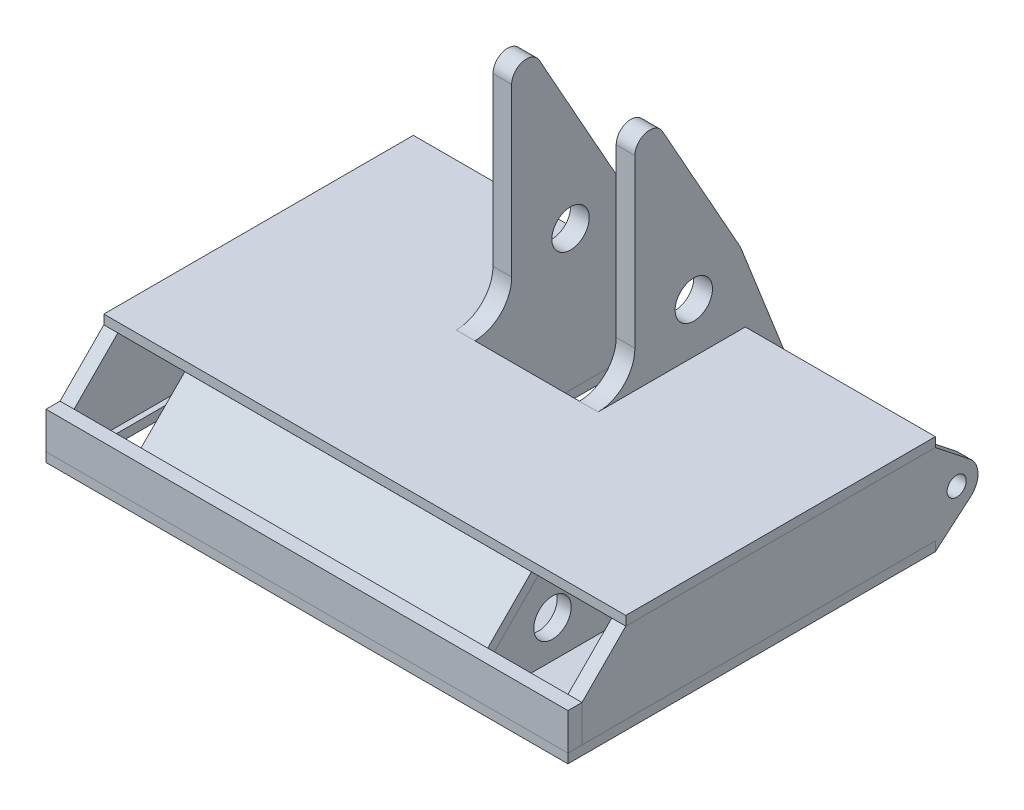
SolidWorks part; units mm, degrees
material "2024-T4"
ref_plane "Front Plane" through (0, 0, 0) normal (0, 0, 1) x (1, 0, 0)
ref_plane "Top Plane" through (0, 0, 0) normal (0, 1, 0) x (1, 0, 0)
ref_plane "Right Plane" through (0, 0, 0) normal (1, 0, 0) x (0, 0, -1)
sketch "Side View" plane through (0, 0, 0) normal (1, 0, 0) x (0, 0, -1)
  line L1 (165, 199.6593) -> (165, 86.35)
  line L3 (140, 55) -> (29.7536, 55)
  line L4 (240, 0) -> (240, 55) construction
  line L5 (0, 0) -> (240, 0)
  line L9 (183.7233, 204.5484) -> (235.5315, 112.1122)
  line L10 (179.9201, 117.2092) -> (110.2141, 38.4935) construction
  line L11 (29.7536, 55) -> (140, 55)
  line L12 (29.7536, 55) -> (29.7536, 61.35) construction
  line L13 (29.7536, 61.35) -> (140, 61.35) construction
  line L14 (140, 55) -> (140, 61.35)
  line L15 (0, 0) -> (240, 0) construction
  line L16 (0, 0) -> (0, -6.35) construction
  line L17 (0, -6.35) -> (240, -6.35) construction
  line L18 (240, 0) -> (240, -6.35) construction
  line L19 (223.5253, 67.0883) -> (135.9217, 8.9446) construction
  line L20 (240, 55) -> (240, 0) construction
  line L21 (240, 0) -> (240, -6.35)
  line L22 (240, 55) -> (230.475, 55) construction
  line L23 (230.475, 55) -> (230.475, 0) construction
  line L24 (13.588, 51.1116) -> (-9.525, 27.8072) construction
  line L25 (240, -6.35) -> (263.8895, 13.9507)
  line L26 (267.9974, 30.2982) -> (237.5799, 107.7886)
  line L27 (13.588, 51.1116) -> (167.8998, 206.7011) construction
  line L28 (190.9625, 46.4) -> (39.5125, 46.4) construction
  line L29 (39.5125, 25.4) -> (190.9625, 25.4) construction
  line L30 (190.9625, 4.4) -> (39.5125, 4.4) construction
  line L31 (-9.525, 25) -> (-9.525, -6.35) construction
  line L32 (-9.525, -6.35) -> (0, -6.35) construction
  line L33 (0, 0) -> (0, 25)
  line L34 (0, 25) -> (29.7536, 55)
  line L35 (-9.525, 25) -> (0, 25) construction
  line L36 (-4.5086, 29.4716) -> (25.245, 59.4716) construction
  line L37 (0, 25) -> (-4.5086, 29.4716) construction
  line L38 (29.7536, 55) -> (25.245, 59.4716) construction
  circle A1 centre (205, 95) radius 12.7
  circle A2 centre (205, 95) radius 100 construction
  arc A3 (183.7233, 204.5484) -> (165, 199.6593) centre (175, 199.6593) ccw
  arc A4 (140, 61.35) -> (165, 86.35) centre (140, 86.35) ccw
  circle A5 centre (125, 25.4) radius 19.75 construction
  circle A6 centre (205, 95) radius 33.5 construction
  circle A7 centre (39.5125, 25.4) radius 36.5125 construction
  circle A8 centre (190.9625, 25.4) radius 36.5125 construction
  circle A9 centre (254.5, 25) radius 6.5
  arc A11 (263.8895, 13.9507) -> (267.9974, 30.2982) centre (254.5, 25) ccw
  arc A13 (237.5799, 107.7886) -> (235.5315, 112.1122) centre (205, 95) ccw
  circle A14 centre (190.9625, 25.4) radius 21 construction
  circle A15 centre (39.5125, 25.4) radius 21 construction
  point P16 (240, 0)
  point P24 (165, 237.9546)
  point P40 (217.1923, 0)
  point P43 (23.0635, 0)
  point P45 (164.7327, 0)
  point P49 (65.7423, 0)
  point P50 (13.2827, 0)
  point P52 (0, 0)
  point P53 (250, 105.4809)
  point P56 (0, 0)
  dimension "D1" = 25.4
  dimension "D3" = 200
  dimension "D8" = 10
  dimension "D11" = 39.5
  dimension "D15" = 67
  dimension "D17" = 73.025
  dimension "D16" = 13
  dimension "D29" = 73.025
  dimension "D31" = 42
  dimension "D32" = 42
  dimension "D28" = 35
  dimension "D2" = 55
  dimension "D9" = 6.35
  dimension "D10" = 25
  dimension "D14" = 40
  dimension "D5" = 5
  dimension "D4" = 35
  dimension "D18" = 4.7625
  dimension "D7" = 5
  dimension "D20" = 3
  dimension "D22" = 25
  dimension "D26" = 9.525
  dimension "D13" = 80
  dimension "D19" = 3
  dimension "D6" = 240
  dimension "D24" = 8
  dimension "D25" = 8
  dimension "D27" = 25
  dimension "D30" = 4.7625
  dimension "D34" = 151.45
  dimension "D21" = 6.35
sketch "Top View" plane through (0, 0, 0) normal (0, 1, 0) x (1, 0, 0)
  line L0 (0, 120) -> (0, 0) construction
  line L1 (177.25, 0) -> (167.725, 0)
  line L2 (177.25, 0) -> (177.25, 240)
  line L3 (177.25, 240) -> (35.5, 240)
  line L4 (-177.25, 0) -> (-177.25, 240)
  line L5 (177.25, 0) -> (-177.25, 240) construction
  line L6 (177.25, 240) -> (-177.25, 0) construction
  line L9 (-35.5, 240) -> (-35.5, 0)
  line L11 (35.5, 240) -> (35.5, 0)
  line L13 (-167.725, 230.475) -> (-167.725, 0)
  line L15 (-117.725, 230.475) -> (-117.725, 0)
  line L17 (167.725, 230.475) -> (117.725, 230.475)
  line L18 (167.725, 230.475) -> (167.725, 0)
  line L19 (-35.5, 240) -> (-177.25, 240)
  line L20 (-167.725, 0) -> (-177.25, 0)
  line L22 (167.725, 230.475) -> (48.2, 230.475)
  line L26 (-48.2, 230.475) -> (-167.725, 230.475)
  line L29 (167.725, 0) -> (-108.2, 0)
  line L33 (-150.8375, 190.9625) -> (-150.8375, 229.0625) construction
  line L35 (-161.95, 77.6125) -> (-161.95, 1.4125) construction
  line L36 (108.2, 165.9625) -> (53.2, 165.9625) construction
  line L37 (-108.2, 215.9625) -> (-53.2, 215.9625) construction
  line L38 (-108.2, 215.9625) -> (-108.2, 165.9625) construction
  line L39 (-108.2, 165.9625) -> (-53.2, 165.9625) construction
  line L40 (-53.2, 215.9625) -> (-53.2, 165.9625) construction
  line L41 (53.2, 215.9625) -> (53.2, 165.9625) construction
  line L42 (108.2, 215.9625) -> (53.2, 215.9625) construction
  line L43 (108.2, 215.9625) -> (108.2, 165.9625) construction
  line L44 (161.95, 152.8625) -> (139.725, 152.8625) construction
  line L45 (-161.95, 229.0625) -> (-139.725, 229.0625) construction
  line L46 (-161.95, 229.0625) -> (-161.95, 152.8625) construction
  line L47 (-161.95, 152.8625) -> (-139.725, 152.8625) construction
  line L48 (-139.725, 229.0625) -> (-139.725, 152.8625) construction
  line L49 (-161.95, 229.0625) -> (-139.725, 152.8625) construction
  line L50 (-161.95, 152.8625) -> (-139.725, 229.0625) construction
  line L51 (139.725, 229.0625) -> (139.725, 152.8625) construction
  line L52 (161.95, 229.0625) -> (139.725, 229.0625) construction
  line L53 (161.95, 229.0625) -> (161.95, 152.8625) construction
  line L54 (-108.2, 240) -> (-108.2, 0) construction
  line L56 (-139.725, 77.6125) -> (-139.725, 1.4125) construction
  line L57 (-48.2, 230.475) -> (-48.2, 0)
  line L58 (48.2, 230.475) -> (48.2, 0)
  line L59 (-108.2, 0) -> (-167.725, 0)
  line L60 (-117.725, 230.475) -> (-117.725, -9.525) construction
  line L61 (105.4111, 240) -> (167.725, 0) construction
  line L62 (-35.5, 240) -> (35.5, 240)
  line L63 (-48.2, 230.475) -> (48.2, 230.475) construction
  line L65 (167.725, 240) -> (105.4111, 240) construction
  line L66 (-167.725, 240) -> (-108.2, 240) construction
  line L67 (-167.725, 230.475) -> (-117.725, 230.475) construction
  line L68 (-161.95, 1.4125) -> (-139.725, 1.4125) construction
  line L69 (-161.95, 39.5125) -> (-139.725, 39.5125) construction
  line L70 (-177.25, 0) -> (-177.25, -9.525)
  line L71 (-119.725, 9.5125) -> (-119.725, 69.5125) construction
  line L72 (-119.725, 160.9625) -> (-139.725, 160.9625) construction
  line L73 (-119.725, 160.9625) -> (-119.725, 220.9625) construction
  line L74 (-119.725, 220.9625) -> (-139.725, 220.9625) construction
  line L75 (-139.725, 160.9625) -> (-139.725, 220.9625) construction
  line L76 (-119.725, 160.9625) -> (-139.725, 220.9625) construction
  line L77 (-119.725, 220.9625) -> (-139.725, 160.9625) construction
  line L78 (-119.725, 9.5125) -> (-139.725, 9.5125) construction
  line L79 (-139.725, 9.5125) -> (-139.725, 69.5125) construction
  line L80 (-119.725, 69.5125) -> (-139.725, 69.5125) construction
  line L81 (-108.2, 230.475) -> (-108.2, 0)
  line L82 (-161.95, 77.6125) -> (-139.725, 77.6125) construction
  line L83 (-161.95, 77.6125) -> (-139.725, 77.6125) construction
  line L84 (-177.25, -9.525) -> (177.25, -9.525)
  line L85 (48.2, 145) -> (155.2, 145) construction
  line L86 (48.2, 145) -> (48.2, 105) construction
  line L87 (48.2, 105) -> (155.2, 105) construction
  line L88 (155.2, 145) -> (155.2, 105) construction
  line L89 (1.5875, 105) -> (-23.8125, 105) construction
  line L90 (1.5875, 105) -> (1.5875, 305) construction
  line L91 (1.5875, 305) -> (-23.8125, 305) construction
  line L92 (-23.8125, 105) -> (-23.8125, 305) construction
  line L93 (1.5875, 105) -> (-23.8125, 305) construction
  line L94 (1.5875, 305) -> (-23.8125, 105) construction
  line L95 (177.25, -9.525) -> (177.25, 0)
  line L96 (0, 105) -> (0, 305) construction
  line L97 (-11.1125, 205) -> (11.1125, 205) construction
  line L98 (20.6375, 171.5) -> (1.5875, 171.5) construction
  line L99 (20.6375, 171.5) -> (20.6375, 238.5) construction
  line L100 (20.6375, 238.5) -> (1.5875, 238.5) construction
  line L101 (1.5875, 171.5) -> (1.5875, 238.5) construction
  line L102 (20.6375, 171.5) -> (1.5875, 238.5) construction
  line L103 (20.6375, 238.5) -> (1.5875, 171.5) construction
  line L104 (180.0389, -9.525) -> (-117.725, -9.525) construction
  line L105 (117.725, 230.475) -> (180.0389, -9.525) construction
  line L106 (119.725, 160.9625) -> (139.725, 160.9625) construction
  line L107 (119.725, 160.9625) -> (119.725, 220.9625) construction
  line L108 (119.725, 220.9625) -> (139.725, 220.9625) construction
  line L109 (108.2, 230.475) -> (108.2, 0)
  line L110 (117.725, 230.475) -> (117.725, 0)
  line L111 (119.725, 9.5125) -> (119.725, 69.5125) construction
  line L112 (119.725, 69.5125) -> (139.725, 69.5125) construction
  line L113 (119.725, 9.5125) -> (139.725, 9.5125) construction
  line L114 (161.95, 1.4125) -> (139.725, 1.4125) construction
  line L115 (161.95, 77.6125) -> (139.725, 77.6125) construction
  line L116 (161.95, 77.6125) -> (161.95, 1.4125) construction
  line L117 (139.725, 77.6125) -> (139.725, 1.4125) construction
  line L118 (-167.725, 230.475) -> (-167.725, 240)
  line L119 (-48.2, 230.475) -> (-48.2, 240)
  line L120 (48.2, 230.475) -> (48.2, 240)
  line L121 (167.725, 230.475) -> (167.725, 240)
  line L122 (0, 171.5) -> (0, 238.5) construction
  line L123 (-35.5, 145) -> (35.5, 145)
  line L125 (-107.2, 162) -> (-51.2, 162) construction
  line L126 (-107.2, 162) -> (-107.2, 2) construction
  line L127 (-107.2, 2) -> (-51.2, 2) construction
  line L128 (-51.2, 162) -> (-51.2, 2) construction
  line L129 (-35.5, 104) -> (35.5, 104)
  line L130 (-35.5, 104) -> (-35.5, 94.475)
  line L131 (-35.5, 94.475) -> (35.5, 94.475)
  line L132 (35.5, 104) -> (35.5, 94.475)
  point P0 (0, 0)
  point P44 (-150.8375, 190.9625)
  point P45 (-167.725, 115.2375)
  point P58 (-129.725, 190.9625)
  point P60 (-53.2, 190.9625)
  point P76 (0, 205)
  point P77 (11.1125, 205)
  point P78 (-11.1125, 205)
  point P87 (155.2, 125)
  dimension "D5" = 50
  dimension "D6" = 9.525
  dimension "D10" = 22.225
  dimension "D11" = 76.2
  dimension "D12" = 50
  dimension "D8" = 9.525
  dimension "D15" = 12.7
  dimension "D7" = 55
  dimension "D4" = 20
  dimension "D14" = 2
  dimension "D16" = 60
  dimension "D3" = 71
  dimension "D18" = 9.525
  dimension "D19" = 40
  dimension "D20" = 107
  dimension "D21" = 25.4
  dimension "D22" = 19.05
  dimension "D24" = 9.525
  dimension "D25" = 60
  dimension "D23" = 56
  dimension "D26" = 160
  dimension "D27" = 2
  dimension "D28" = 3
  dimension "D29" = 9.525
  dimension "D30" = 1
  dimension "D31" = 60
  dimension "D32" = 354.5
  dimension "D9" = 9.525
  dimension "D13" = 2
  dimension "D17" = 2
ref_plane "Left Weapon Wall Plane" through (-35.5, 0, 0) normal (1, 0, 0) x (0, 0, -1)
ref_plane "Right Weapon Wall Plane" through (35.5, 0, 0) normal (1, 0, 0) x (0, 0, -1)
ref_plane "Front Wall Plane" through (0, 0, -240) normal (0, 0, 1) x (1, 0, 0)
ref_plane "Rear Wall Plane" through (0, 0, 9.525) normal (0, 0, 1) x (1, 0, 0)
ref_plane "Left Motor Wall Plane" through (-108.2, 0, 0) normal (1, 0, 0) x (0, 0, -1)
ref_plane "Right Motor Wall Plane" through (108.2, 0, 0) normal (1, 0, 0) x (0, 0, -1)
ref_plane "Left Outside Wall Plane" through (-177.25, 0, 0) normal (1, 0, 0) x (0, 0, -1)
ref_plane "Wheel Center" through (-150.8375, 0, 0) normal (1, 0, 0) x (0, 0, -1)
ref_plane "Angled Back Plane" through (0, 12.3969, 12.4996) normal (0, -0.7042, -0.71) x (0, 0.71, -0.7042)
ref_plane "Top Plate Plane" through (0, 55, 0) normal (0, 1, 0) x (1, 0, 0)
ref_plane "Shielding Plate Plane" through (0, 0, -104) normal (0, 0, 1) x (1, 0, 0)
sketch "Sketch14" plane through (0, 0, -104) normal (0, 0, 1) x (1, 0, 0)
  line L1 (-35.5, 0) -> (35.5, 0)
  line L2 (-35.5, 0) -> (-35.5, 55)
  line L3 (-35.5, 55) -> (35.5, 55)
  line L4 (35.5, 0) -> (35.5, 55)
extrude "Boss-Extrude9" add sketch "Sketch14" along normal up to vertex (9.525 mm away) up to point (-35.5, 0, -94.475)
sketch "Sketch2" plane through (0, 0, 0) normal (0, 1, 0) x (1, 0, 0)
  line L0 (177.25, -9.525) -> (177.25, 0) construction
  line L1 (-177.25, 0) -> (-177.25, -9.525) construction
  line L2 (-177.25, -9.525) -> (177.25, -9.525) construction
  line L3 (177.25, 0) -> (177.25, 240) construction
  line L4 (177.25, 240) -> (35.5, 240) construction
  line L5 (35.5, 240) -> (35.5, 0) construction
  line L6 (-35.5, 145) -> (35.5, 145) construction
  line L7 (-35.5, 240) -> (-35.5, 0) construction
  line L8 (-35.5, 240) -> (-177.25, 240) construction
  line L9 (-177.25, 0) -> (-177.25, 240) construction
  line L10 (177.25, -9.525) -> (177.25, 0)
  line L11 (-177.25, 0) -> (-177.25, -9.525)
  line L12 (-177.25, -9.525) -> (177.25, -9.525)
  line L13 (177.25, 0) -> (177.25, 240)
  line L14 (177.25, 240) -> (35.5, 240)
  line L15 (35.5, 240) -> (35.5, 145)
  line L16 (-35.5, 145) -> (35.5, 145)
  line L17 (-35.5, 240) -> (-35.5, 145)
  line L18 (-35.5, 240) -> (-177.25, 240)
  line L19 (-177.25, 0) -> (-177.25, 240)
  line L20 (-161.95, 1.4125) -> (-139.725, 1.4125) construction
  line L21 (-139.725, 77.6125) -> (-139.725, 1.4125) construction
  line L22 (-161.95, 77.6125) -> (-139.725, 77.6125) construction
  line L23 (-161.95, 77.6125) -> (-161.95, 1.4125) construction
  line L24 (-139.725, 229.0625) -> (-139.725, 152.8625) construction
  line L25 (-163.95, 219.1923) -> (-137.725, 219.1923)
  line L26 (-137.725, 219.1923) -> (-137.725, 162.7327)
  line L27 (-161.95, 229.0625) -> (-161.95, 152.8625) construction
  line L28 (-161.95, 1.4125) -> (-139.725, 1.4125) construction
  line L29 (-139.725, 77.6125) -> (-139.725, 1.4125) construction
  line L30 (-161.95, 77.6125) -> (-139.725, 77.6125) construction
  line L31 (-161.95, 77.6125) -> (-161.95, 1.4125) construction
  line L32 (-139.725, 217.1923) -> (-139.725, 164.7327) construction
  line L35 (-161.95, 217.1923) -> (-161.95, 164.7327) construction
  line L36 (-161.95, 217.1923) -> (-139.725, 217.1923) construction
  line L37 (-150.8375, 190.9625) -> (-129.725, 190.9625) construction
  line L38 (-161.95, 164.7327) -> (-139.725, 164.7327) construction
  line L39 (-163.95, 162.7327) -> (-137.725, 162.7327)
  line L40 (-163.95, 219.1923) -> (-163.95, 162.7327)
  line L41 (-137.725, 67.7423) -> (-137.725, 11.2827)
  line L42 (-163.95, 67.7423) -> (-137.725, 67.7423)
  line L43 (-163.95, 67.7423) -> (-163.95, 11.2827)
  line L44 (-163.95, 11.2827) -> (-137.725, 11.2827)
  line L45 (-150.8375, 39.5125) -> (-129.725, 39.5125) construction
  line L46 (-161.95, 39.5125) -> (-139.725, 39.5125) construction
  dimension "D1" = 2
  dimension "D2" = 2
extrude "Bottom Plate" add sketch "Sketch2" against normal up to vertex (6.35 mm away) up to point (0, -6.35, 0)
sketch "Sketch3" plane through (-35.5, 0, 0) normal (1, 0, 0) x (0, 0, -1)
  line L0 (140, 55) -> (29.7536, 55) construction
  line L2 (140, 55) -> (140, 61.35) construction
  line L3 (165, 199.6593) -> (165, 86.35) construction
  line L4 (183.7233, 204.5484) -> (235.5315, 112.1122) construction
  line L7 (0, 0) -> (240, 0) construction
  line L8 (0, 0) -> (0, 25) construction
  line L9 (0, 25) -> (29.7536, 55) construction
  line L10 (140, 55) -> (29.7536, 55)
  line L12 (140, 55) -> (140, 61.35)
  line L13 (165, 199.6593) -> (165, 86.35)
  line L14 (183.7233, 204.5484) -> (235.5315, 112.1122)
  line L17 (0, 0) -> (240, 0)
  line L18 (0, 0) -> (0, 25)
  line L19 (0, 25) -> (29.7536, 55)
  line L20 (240, 0) -> (240, -6.35) construction
  line L21 (240, -6.35) -> (263.8895, 13.9507) construction
  line L22 (267.9974, 30.2982) -> (237.5799, 107.7886) construction
  line L23 (240, 0) -> (240, -6.35)
  line L24 (240, -6.35) -> (263.8895, 13.9507)
  line L25 (267.9974, 30.2982) -> (237.5799, 107.7886)
  arc A0 (140, 61.35) -> (165, 86.35) centre (140, 86.35) ccw construction
  arc A1 (183.7233, 204.5484) -> (165, 199.6593) centre (175, 199.6593) ccw construction
  arc A3 (140, 61.35) -> (165, 86.35) centre (140, 86.35) ccw
  arc A4 (183.7233, 204.5484) -> (165, 199.6593) centre (175, 199.6593) ccw
  circle A6 centre (205, 95) radius 12.7 construction
  circle A7 centre (205, 95) radius 12.7
  arc A8 (263.8895, 13.9507) -> (267.9974, 30.2982) centre (254.5, 25) ccw construction
  arc A9 (263.8895, 13.9507) -> (267.9974, 30.2982) centre (254.5, 25) ccw
  arc A12 (237.5799, 107.7886) -> (235.5315, 112.1122) centre (205, 95) ccw construction
  arc A13 (237.5799, 107.7886) -> (235.5315, 112.1122) centre (205, 95) ccw
  circle A14 centre (254.5, 25) radius 6.5 construction
  circle A15 centre (254.5, 25) radius 6.5
extrude "Left Weapon Wall" add sketch "Sketch3" against normal up to vertex (12.7 mm away) separate body up to point (-48.2, 0, 0)
sketch "Sketch5" plane through (-177.25, 0, 0) normal (1, 0, 0) x (0, 0, -1)
  line L1 (0, 0) -> (240, 0) construction
  line L2 (0, 0) -> (0, 25) construction
  line L3 (0, 25) -> (29.7536, 55) construction
  line L4 (140, 55) -> (29.7536, 55) construction
  line L6 (0, 0) -> (240, 0)
  line L7 (0, 0) -> (0, 25)
  line L8 (0, 25) -> (29.7536, 55)
  line L9 (240, 55) -> (29.7536, 55)
  line L10 (240, -6.35) -> (263.8895, 13.9507) construction
  line L11 (240, 0) -> (240, -6.35) construction
  line L12 (240, -6.35) -> (263.8895, 13.9507)
  line L13 (240, 0) -> (240, -6.35)
  line L14 (263.5082, 36.3623) -> (240, 55)
  line L15 (240, 55) -> (230.475, 55) construction
  arc A0 (263.8895, 13.9507) -> (267.9974, 30.2982) centre (254.5, 25) ccw construction
  arc A1 (263.8895, 13.9507) -> (263.5082, 36.3623) centre (254.5, 25) ccw
  circle A2 centre (254.5, 25) radius 6.5 construction
  circle A3 centre (254.5, 25) radius 6.5
  point P6 (39.5125, 25.4)
  point P8 (190.9625, 25.4)
extrude "Left Wall" add sketch "Sketch5" along normal up to vertex (9.525 mm away) separate body up to point (-167.725, 0, 0)
sketch "Sketch6" plane through (-108.2, 0, 0) normal (1, 0, 0) x (0, 0, -1)
  line L1 (240, 0) -> (-9.525, 0) construction
  line L2 (0, 0) -> (0, 25) construction
  line L3 (0, 25) -> (29.7536, 55) construction
  line L4 (140, 55) -> (29.7536, 55) construction
  line L6 (230.475, 0) -> (0, 0)
  line L7 (0, 0) -> (0, 25)
  line L8 (0, 25) -> (29.7536, 55)
  line L9 (230.475, 55) -> (29.7536, 55)
  line L10 (230.475, 55) -> (230.475, 0) construction
  line L11 (230.475, 55) -> (230.475, 0)
extrude "Left Motor Wall" add sketch "Sketch6" against normal up to vertex (9.525 mm away) separate body up to point (-117.725, 0, 0)
sketch "Sketch7" plane through (0, 0, 9.525) normal (0, 0, 1) x (1, 0, 0)
  line L1 (-177.25, 0) -> (177.25, 0) construction
  line L2 (-177.25, 0) -> (177.25, 0)
  line L4 (-177.25, 0) -> (177.25, 0)
  line L5 (-177.25, 0) -> (-177.25, 25)
  line L6 (-177.25, 25) -> (177.25, 25)
  line L7 (177.25, 0) -> (177.25, 25)
  point P0 (0, 25)
extrude "Rear Wall" add sketch "Sketch7" against normal up to vertex (9.525 mm away) separate body contours L2 L7 L6 L5 up to point (0, 0, 0)
sketch "Sketch8" plane through (0, 0, -240) normal (0, 0, 1) x (1, 0, 0)
  line L0 (-35.5, 0) -> (-177.25, 0) construction
  line L1 (-48.2, 0) -> (-167.725, 0)
  line L3 (-48.2, 0) -> (-167.725, 0)
  line L5 (-48.2, 55) -> (-167.725, 55)
  line L8 (-48.2, 55) -> (-48.2, 0)
  line L9 (-167.725, 0) -> (-167.725, 55)
  point P0 (0, 55)
  point P10 (-167.725, 0)
extrude "Boss-Extrude6" add sketch "Sketch8" along normal up to vertex (9.525 mm away) separate body up to point (-48.2, 0, -230.475)
mirror "Mirror1" about plane through (0, 0, 0) normal (1, 0, 0) of bodies 103 106 102 104
sketch "Sketch10" plane through (108.2, 0, 0) normal (-1, 0, 0) x (0, 0, 1)
  circle A0 centre (-190.9625, 25.4) radius 12.7
  circle A1 centre (-39.5125, 25.4) radius 12.7
  circle A2 centre (-125, 25.4) radius 20.5
  dimension "D1" = 25.4
  dimension "D2" = 41
extrude "Cut-Extrude1" cut sketch "Sketch10" against normal up to next (9.525 mm away)
sketch "Sketch11" plane through (-117.725, 0, 0) normal (-1, 0, 0) x (0, 0, 1)
  circle A0 centre (-39.5125, 25.4) radius 12.7 construction
  circle A1 centre (-190.9625, 25.4) radius 12.7 construction
  circle A2 centre (-39.5125, 25.4) radius 12.7
  circle A3 centre (-190.9625, 25.4) radius 12.7
extrude "Cut-Extrude2" cut sketch "Sketch11" against normal up to next (9.525 mm away)
sketch "Sketch12" plane through (0, 12.3969, 12.4996) normal (0, -0.7042, -0.71) x (0, 0.71, -0.7042)
  line L1 (60.003, 117.725) -> (17.7504, 117.725)
  line L2 (60.003, 117.725) -> (60.003, -117.725)
  line L3 (60.003, -117.725) -> (17.7504, -117.725)
  line L4 (17.7504, 117.725) -> (17.7504, -117.725)
  line L5 (162.2971, -117.725) -> (0, -117.725) construction
  line L8 (0, 0) -> (60.003, 0) construction
  line L9 (-4.5086, 0) -> (164.4959, 0) construction
extrude "Rear Angled Plate" add sketch "Sketch12" against normal up to vertex (6.35 mm away) separate body up to point (0, 59.4716, -25.245)
sketch "Sketch13" plane through (0, 55, 0) normal (0, 1, 0) x (1, 0, 0)
  line L25 (0, 140) -> (0, 29.7536) construction
  line L26 (-48.2, 230.475) -> (-48.2, 0) construction
  line L27 (-48.2, 230.475) -> (-48.2, 240) construction
  line L28 (-35.5, 240) -> (-177.25, 240) construction
  line L29 (-177.25, 0) -> (-177.25, 240) construction
  line L31 (177.25, 29.7536) -> (177.25, 240)
  line L33 (48.2, 240) -> (177.25, 240)
  line L34 (0, 140) -> (0, 29.7536) construction
  line L35 (-48.2, 230.475) -> (-48.2, 140)
  line L36 (-48.2, 230.475) -> (-48.2, 240)
  line L37 (-48.2, 240) -> (-177.25, 240)
  line L38 (-177.25, 29.7536) -> (-177.25, 240)
  line L40 (-48.2, 140) -> (48.2, 140)
  line L43 (-177.25, 29.7536) -> (177.25, 29.7536)
  line L44 (48.2, 230.475) -> (48.2, 240)
  line L45 (48.2, 230.475) -> (48.2, 140)
  line L50 (-117.725, 29.7536) -> (117.725, 29.7536) construction
extrude "Top Plate" add sketch "Sketch13" along normal up to vertex (6.35 mm away) separate body up to point (0, 61.35, -29.7536)
sketch "Sketch15" plane through (48.2, 0, 0) normal (1, 0, 0) x (0, 0, -1)
  circle A0 centre (125, 25.4) radius 19.75 construction
  circle A1 centre (125, 25.4) radius 19.75 construction
  circle A2 centre (125, 25.4) radius 20.5
  dimension "D1" = 41
extrude "Cut-Extrude3" cut sketch "Sketch15" against normal up to surface (12.7 mm away) up to face at (35.5, 25, -261)
equation "\"D8@Top View\"=\"D9@Top View\""
equation "\"D18@Top View\"=\"D8@Top View\""
equation "\"D24@Top View\"=\"D8@Top View\""
equation "\"D19@Side View\"=\"D20@Side View\""
equation "\"D29@Top View\"=\"D18@Top View\""
equation "\"D30@Side View\"=\"D18@Side View\""
equation "\"D31@Side View\"=\"D32@Side View\""
